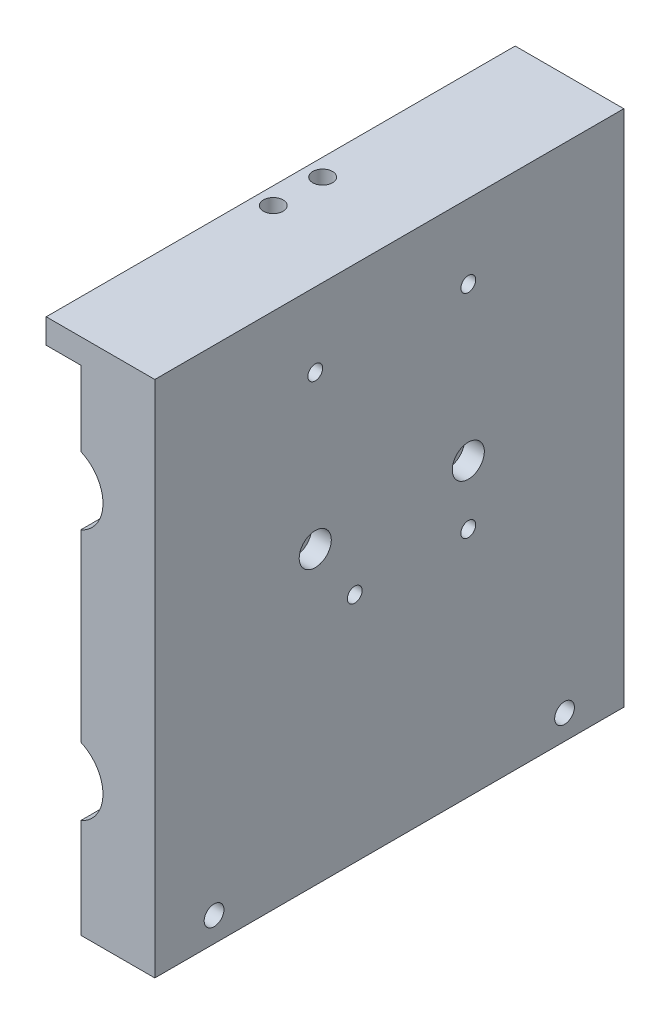
SolidWorks part; units mm, degrees
material "ABS"
ref_plane "Front Plane" through (0, 0, 0) normal (0, 0, 1) x (1, 0, 0)
ref_plane "Top Plane" through (0, 0, 0) normal (0, 1, 0) x (1, 0, 0)
ref_plane "Right Plane" through (0, 0, 0) normal (1, 0, 0) x (0, 0, -1)
sketch "Sketch1" plane through (0, 0, 0) normal (0, 0, 1) x (1, 0, 0)
  line L0 (0, 0) -> (0, -37.75)
  line L4 (0, -37.75) -> (0, -100)
  line L5 (0, -100) -> (15, -100)
  line L6 (15, -100) -> (15, 5)
  line L7 (15, 5) -> (-7, 5)
  line L8 (-7, 5) -> (-7, 0)
  line L9 (-7, 0) -> (0, 0)
  dimension "D1" = 15
  dimension "D3" = 7
  dimension "D4" = 5
  dimension "D5" = 37.75
  dimension "D6" = 105
extrude "Boss-Extrude1" add sketch "Sketch1" along normal blind 95
ref_plane "Plan6" through (0, -47.5, 0) normal (0, 1, 0) x (1, 0, 0)
ref_plane "Plan3" through (0, 0, 47.5) normal (0, 0, -1) x (-1, 0, 0)
sketch "Sketch2" plane through (0, 0, 0) normal (-1, 0, 0) x (0, 0, 1)
  line L0 (95, 5) -> (0, 5) construction
  line L2 (47.5, 5) -> (47.5, -173.9913) construction
  line L3 (12.1, -47.5) -> (-12.1, -47.5) construction
  circle A1 centre (62.5, -41) radius 2
  circle A2 centre (31.5, -41) radius 2
  dimension "D2" = 4
  dimension "D4" = 31
  dimension "D5" = 15
  dimension "D6" = 6.5
extrude "Cut-Extrude1 3dprinter4" cut sketch "Sketch2" against normal through all
sketch "Esquisse1" plane through (15, 0, 0) normal (1, 0, 0) x (0, 0, -1)
  line L2 (-47.5, -12.1) -> (-47.5, 12.1) construction
  line L3 (12.1, -47.5) -> (-12.1, -47.5) construction
  circle A0 centre (-62.5, -10) radius 1.5
  circle A1 centre (-31.5, -10) radius 1.5
  circle A4 centre (-54.5, -53) radius 1.5
  circle A5 centre (-31.5, -53) radius 1.5
  dimension "D1" = 15
  dimension "D2" = 37.5
  dimension "D3" = 31
  dimension "D4" = 43
  dimension "D5" = 3
  dimension "D6" = 8
  dimension "D7" = 23
extrude "Enlèv. mat.-Extru.1 3d printer" cut sketch "Esquisse1" against normal through all
sketch "Esquisse2" plane through (0, 0, 0) normal (-1, 0, 0) x (0, 0, 1)
  circle A0 centre (62.5, -10) radius 2.5
  circle A1 centre (31.5, -10) radius 2.5
  dimension "D1" = 5
extrude "Enlèv. mat.-Extru.2" cut sketch "Esquisse2" against normal blind 3 and the other way through all
sketch "Esquisse3" plane through (15, 0, 0) normal (1, 0, 0) x (0, 0, -1)
  circle A1 centre (-31.5, -41) radius 3.25
  circle A2 centre (-62.5, -41) radius 3.25
  dimension "D1" = 6.5
extrude "Enlèv. mat.-Extru.3" cut sketch "Esquisse3" against normal blind 4
sketch "Esquisse4" plane through (15, 0, 0) normal (1, 0, 0) x (0, 0, -1)
  line L0 (-95, -100) -> (-95, 5) construction
  line L1 (0, -100) -> (0, 5) construction
  line L2 (-95, -100) -> (0, -100) construction
  circle A0 centre (-83, -95) radius 2
  circle A1 centre (-12, -95) radius 2
  circle A2 centre (-12, -95) radius 3.25
  circle A3 centre (-83, -95) radius 3.25
  dimension "D1" = 4
  dimension "D2" = 12
  dimension "D3" = 12
  dimension "D4" = 5
  dimension "D5" = 6.5
extrude "Enlèv. mat.-Extru.4" cut sketch "Esquisse4" against normal through all contours A0 | A1
sketch "Esquisse8" plane through (0, 0, 0) normal (0, 0, -1) x (-1, 0, 0)
  line L1 (-15, -100) -> (-15, 5) construction
  line L4 (12.1, -47.5) -> (-12.1, -47.5) construction
  circle A0 centre (3, -22) radius 7.5
  circle A1 centre (3, -73) radius 7.5
  dimension "D1" = 25.5
  dimension "D2" = 18
  dimension "D3" = 15
  dimension "D4" = 25.5
extrude "Enlèv. mat.-Extru.9" cut sketch "Esquisse8" against normal through all
sketch "Esquisse9" plane through (15, 0, 0) normal (1, 0, 0) x (0, 0, -1)
  line L0 (0, -100) -> (0, 5) construction
  line L1 (-95, 5) -> (0, 5) construction
  circle A0 centre (-15, -5) radius 4
  circle A1 centre (-80, -5) radius 4
  circle A2 centre (-80, -40) radius 4
  circle A3 centre (-15, -40) radius 4
  circle A4 centre (-22.5, -87) radius 4
  circle A5 centre (-72.5, -87) radius 4
  dimension "D1" = 8
  dimension "D2" = 15
  dimension "D3" = 10
  dimension "D6" = 65
  dimension "D7" = 35
  dimension "D8" = 82
  dimension "D9" = 7.5
  dimension "D11" = 50
  dimension "D4" = 2
  dimension "D5" = 2
  dimension "D10" = 2
sketch "Esquisse10" plane through (0, 0, 0) normal (0, -1, 0) x (1, 0, 0)
  line L0 (-12.1, 47.5) -> (12.1, 47.5) construction
  line L1 (-7, 95) -> (-7, 0) construction
  circle A0 centre (-3.5, 52.5) radius 2
  circle A1 centre (-3.5, 42.5) radius 2
  dimension "D1" = 4
  dimension "D2" = 5
  dimension "D3" = 5
  dimension "D4" = 3.5
extrude "Enlèv. mat.-Extru.10" cut sketch "Esquisse10" against normal through all
sketch "Esquisse11" plane through (0, 0, 0) normal (-1, 0, 0) x (0, 0, 1)
  circle A0 centre (54.5, -53) radius 2.5
  circle A1 centre (31.5, -53) radius 2.5
  dimension "D1" = 5
extrude "Enlèv. mat.-Extru.11" cut sketch "Esquisse11" against normal blind 5
sketch "Esquisse12" plane through (0, 0, 0) normal (-1, 0, 0) x (0, 0, 1)
  circle A1 centre (62.5, -41) radius 3
  circle A2 centre (31.5, -41) radius 3
  dimension "D2" = 6
extrude "Enlèv. mat.-Extru.12" cut sketch "Esquisse12" against normal blind 4
